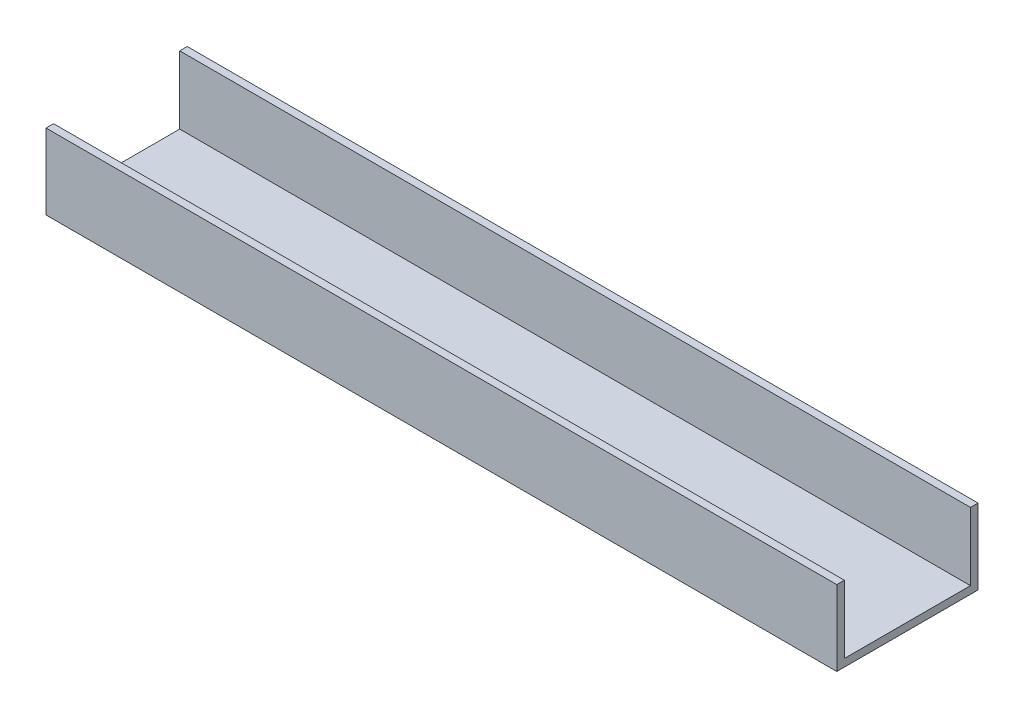
SolidWorks part; units mm, degrees
ref_plane "정면" through (0, 0, 0) normal (0, 0, 1) x (1, 0, 0)
ref_plane "윗면" through (0, 0, 0) normal (0, 1, 0) x (1, 0, 0)
ref_plane "우측면" through (0, 0, 0) normal (1, 0, 0) x (0, 0, -1)
sketch "스케치1" plane through (0, 0, 0) normal (0, 1, 0) x (1, 0, 0)
  line L1 (0, 0) -> (420, 0)
  line L2 (0, 0) -> (0, 75)
  line L3 (0, 75) -> (420, 75)
  line L4 (420, 0) -> (420, 75)
  dimension "D1" = 420
  dimension "D2" = 75
extrude "보스-돌출1" add sketch "스케치1" along normal blind 4
sketch "스케치2" plane through (0, 4, 0) normal (0, 1, 0) x (1, 0, 0)
  line L0 (420, 0) -> (420, 75) construction
  line L1 (0, 0) -> (420, 0)
  line L2 (0, 0) -> (0, 4)
  line L3 (0, 4) -> (420, 4)
  line L4 (420, 0) -> (420, 4)
  line L5 (0, 75) -> (0, 0) construction
  line L6 (420, 75) -> (0, 75)
  line L7 (420, 75) -> (420, 71)
  line L8 (420, 71) -> (0, 71)
  line L9 (0, 75) -> (0, 71)
  dimension "D1" = 4
  dimension "D2" = 4
extrude "보스-돌출2" add sketch "스케치2" along normal blind 36
